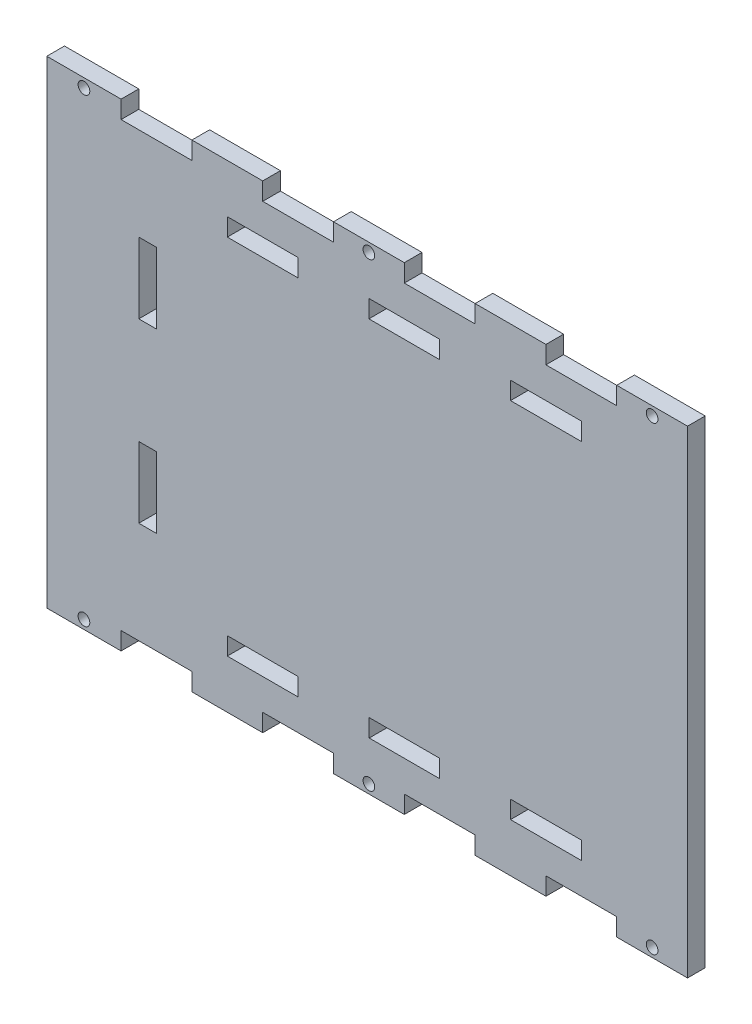
SolidWorks part; units mm, degrees
ref_plane "Front Plane" through (0, 0, 0) normal (0, 0, 1) x (1, 0, 0)
ref_plane "Top Plane" through (0, 0, 0) normal (0, 1, 0) x (1, 0, 0)
ref_plane "Right Plane" through (0, 0, 0) normal (1, 0, 0) x (0, 0, -1)
sketch "Sketch1" plane through (0, 0, 0) normal (0, 0, 1) x (1, 0, 0)
  line L1 (90.51, 155.575) -> (-139.3499, 155.575)
  line L2 (90.51, 155.575) -> (90.51, -15.875)
  line L3 (90.51, -15.875) -> (-139.3499, -15.875)
  line L4 (-139.3499, 155.575) -> (-139.3499, -15.875)
extrude "Boss-Extrude1" add sketch "Sketch1" along normal blind 6.35
sketch "Sketch2" plane through (0, 0, 6.35) normal (0, 0, 1) x (1, 0, 0)
  line L0 (-139.3499, -15.875) -> (90.51, -15.875) construction
  line L1 (-112.69, -9.525) -> (-87.29, -9.525)
  line L2 (-112.69, -9.525) -> (-112.69, -15.875)
  line L3 (-112.69, -15.875) -> (-87.29, -15.875)
  line L4 (-87.29, -9.525) -> (-87.29, -15.875)
  line L5 (-87.29, -9.525) -> (-87.29, -15.875) construction
  line L6 (90.51, 155.575) -> (-139.3499, 155.575) construction
  line L7 (-112.69, 149.225) -> (-87.29, 149.225)
  line L8 (-112.69, 149.225) -> (-112.69, 155.575)
  line L9 (-112.69, 155.575) -> (-87.29, 155.575)
  line L10 (-87.29, 149.225) -> (-87.29, 155.575)
  line L11 (-87.29, 149.225) -> (-87.29, 155.575) construction
extrude "Cut-Extrude1" cut sketch "Sketch2" against normal blind 6.35
pattern_linear "LPattern1" count 4 spacing 50.8 along (1, 0, 0) of "Cut-Extrude1"
sketch "Sketch4" plane through (0, 0, 0) normal (0, 0, -1) x (-1, 0, 0)
  line L0 (128.1535, -9.525) -> (123.8863, -15.875) construction
  line L1 (139.3499, -15.875) -> (112.69, -15.875) construction
  line L2 (123.8863, -9.525) -> (123.8863, -15.875) construction
  line L3 (123.8863, -9.525) -> (128.1535, -15.875) construction
  line L4 (128.1535, -9.525) -> (128.1535, -15.875) construction
  line L5 (21.6564, -9.525) -> (25.9236, -15.875) construction
  line L6 (36.49, -15.875) -> (11.09, -15.875) construction
  line L7 (25.9236, -9.525) -> (25.9236, -15.875) construction
  line L8 (25.9236, -9.525) -> (21.5469, -15.875) construction
  line L9 (-75.6764, -9.525) -> (-79.9436, -15.875) construction
  line L10 (-65.11, -15.875) -> (-90.51, -15.875) construction
  line L11 (-79.9436, -9.525) -> (-79.9436, -15.875) construction
  line L12 (-79.9436, -9.525) -> (-75.7859, -15.875) construction
  line L13 (123.8863, 149.225) -> (128.1535, 155.575) construction
  line L14 (112.69, 155.575) -> (139.3499, 155.575) construction
  line L15 (128.1535, 149.225) -> (128.1535, 155.575) construction
  line L16 (128.1535, 149.225) -> (123.8316, 155.575) construction
  line L17 (21.6564, 149.225) -> (25.9236, 155.575) construction
  line L18 (11.09, 155.575) -> (36.49, 155.575) construction
  line L19 (25.9236, 149.225) -> (25.9236, 155.575) construction
  line L20 (25.9236, 149.225) -> (21.6564, 155.575) construction
  line L21 (-75.6764, 149.225) -> (-79.9436, 155.575) construction
  line L22 (-90.51, 155.575) -> (-65.11, 155.575) construction
  line L23 (-79.9436, 149.225) -> (-75.6764, 155.575) construction
  line L24 (-75.6764, 149.225) -> (-75.6764, 155.575) construction
  circle A0 centre (-77.81, -12.7) radius 2.0955
  circle A1 centre (23.79, -12.7) radius 2.0955
  circle A2 centre (126.0199, -12.7) radius 2.0955
  circle A3 centre (126.0199, 152.4) radius 2.0955
  circle A4 centre (23.79, 152.4) radius 2.0955
  circle A5 centre (-77.81, 152.4) radius 2.0955
  dimension "D1" = 4.191
extrude "Cut-Extrude2" cut sketch "Sketch4" against normal through all
sketch "Sketch5" plane through (0, 0, 0) normal (0, 0, -1) x (-1, 0, 0)
  line L0 (-1.61, 7.9375) -> (23.79, 7.9375) construction
  line L1 (-52.41, 1.5875) -> (-27.01, 1.5875)
  line L2 (-52.41, 1.5875) -> (-52.41, 7.9375)
  line L3 (-52.41, 7.9375) -> (-27.01, 7.9375)
  line L4 (-27.01, 1.5875) -> (-27.01, 7.9375)
  line L5 (-1.61, 1.5875) -> (23.6805, 1.5875)
  line L6 (-1.61, 1.5875) -> (-1.61, 7.9375)
  line L7 (-1.61, 7.9375) -> (23.6805, 7.9375)
  line L8 (23.6805, 1.5875) -> (23.6805, 7.9375)
  line L9 (106.34, 90.4875) -> (106.34, 115.8875) construction
  line L10 (49.19, 1.5875) -> (74.59, 1.5875)
  line L11 (49.19, 1.5875) -> (49.19, 7.9375)
  line L12 (49.19, 7.9375) -> (74.59, 7.9375)
  line L13 (74.59, 1.5875) -> (74.59, 7.9375)
  line L14 (99.99, 26.9875) -> (106.34, 26.9875)
  line L15 (99.99, 26.9875) -> (99.99, 52.3875)
  line L16 (99.99, 52.3875) -> (106.34, 52.3875)
  line L17 (106.34, 26.9875) -> (106.34, 52.3875)
  line L18 (99.99, 90.4875) -> (106.34, 90.4875)
  line L19 (99.99, 90.4875) -> (99.99, 115.8875)
  line L20 (99.99, 115.8875) -> (106.34, 115.8875)
  line L21 (106.34, 90.4875) -> (106.34, 115.8875)
  line L22 (106.34, 115.8875) -> (99.99, 115.8875) construction
  line L24 (49.19, 131.7625) -> (74.59, 131.7625)
  line L25 (49.19, 131.7625) -> (49.19, 138.1125)
  line L26 (49.19, 138.1125) -> (74.59, 138.1125)
  line L27 (74.59, 131.7625) -> (74.59, 138.1125)
  line L28 (-1.61, 131.7625) -> (23.79, 131.7625)
  line L29 (-1.61, 131.7625) -> (-1.61, 138.1125)
  line L30 (-1.61, 138.1125) -> (23.79, 138.1125)
  line L31 (23.79, 131.7625) -> (23.79, 138.1125)
  line L32 (-27.01, 138.1125) -> (-52.41, 138.1125)
  line L33 (-27.01, 138.1125) -> (-27.01, 131.7625)
  line L34 (-27.01, 131.7625) -> (-52.41, 131.7625)
  line L35 (-52.41, 138.1125) -> (-52.41, 131.7625)
extrude "Cut-Extrude3" cut sketch "Sketch5" against normal blind 6.35
